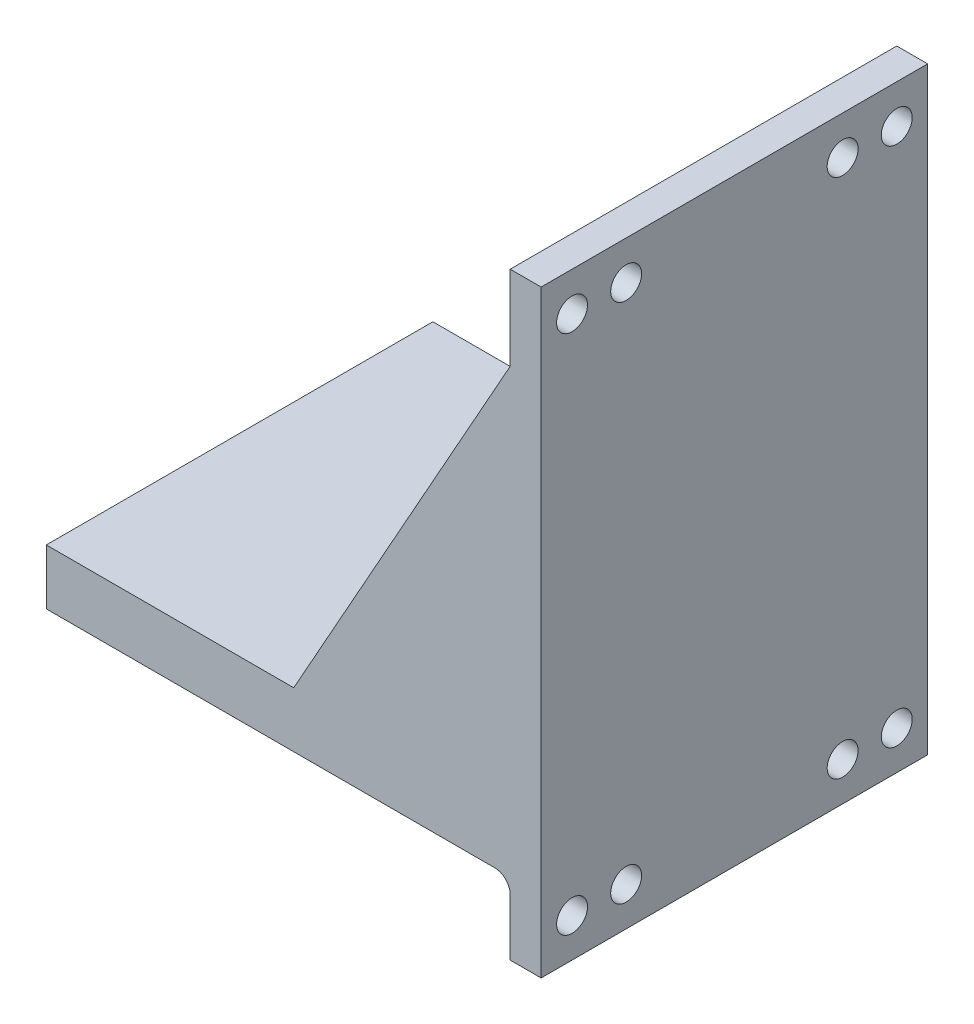
SolidWorks part; units mm, degrees
ref_plane "Front Plane" through (0, 0, 0) normal (0, 0, 1) x (1, 0, 0)
ref_plane "Top Plane" through (0, 0, 0) normal (0, 1, 0) x (1, 0, 0)
ref_plane "Right Plane" through (0, 0, 0) normal (1, 0, 0) x (0, 0, -1)
sketch "Sketch1" plane through (-8, 0, 0) normal (-1, 0, 0) x (0, 0, 1)
  line L0 (30.1107, -33.7) -> (80.1107, -33.7) construction
  line L6 (30.1107, 0) -> (80.1107, 0) construction
  line L8 (30.1107, 38.7) -> (80.1107, 38.7)
  line L9 (30.1107, 38.7) -> (30.1107, -38.7)
  line L10 (30.1107, -38.7) -> (80.1107, -38.7)
  line L11 (80.1107, 38.7) -> (80.1107, -38.7)
  circle A0 centre (34.1107, 33.7) radius 2
  circle A1 centre (41.1107, 33.7) radius 2
  circle A2 centre (69.1107, 33.7) radius 2
  circle A3 centre (76.1107, 33.7) radius 2
  circle A4 centre (34.1107, -33.7) radius 2
  circle A5 centre (41.1107, -33.7) radius 2
  circle A6 centre (69.1107, -33.7) radius 2
  circle A7 centre (76.1107, -33.7) radius 2
  dimension "D1" = 4
  dimension "D2" = 5
extrude "Boss-Extrude1" add sketch "Sketch1" along normal blind 4
sketch "Sketch2" plane through (-12, 0, 0) normal (-1, 0, 0) x (0, 0, 1)
  line L0 (80.1107, -38.7) -> (80.1107, 38.7) construction
  line L1 (80.1107, -29.3571) -> (30.1107, -29.3571)
  line L2 (80.1107, -29.3571) -> (80.1107, -22.1888)
  line L3 (80.1107, -22.1888) -> (30.1107, -22.1888)
  line L4 (30.1107, -29.3571) -> (30.1107, -22.1888)
  line L5 (30.1107, 38.7) -> (30.1107, -38.7) construction
  line L6 (30.1107, -38.7) -> (80.1107, -38.7) construction
  dimension "D1" = 7.1683
  dimension "D2" = 9.3429
extrude "Boss-Extrude2" add sketch "Sketch2" along normal blind 60
ref_plane "Plane1" through (-72, -22.1888, 80.1107) normal (1, 0, 0) x (0, 0, -1)
sketch "Sketch4" plane through (0, 0, 80.1107) normal (0, 0, 1) x (1, 0, 0)
  line L0 (-72, -29.3571) -> (-12, -29.3571) construction
  line L1 (-72, -22.1888) -> (-42, -22.1888)
  line L2 (-72, -22.1888) -> (-72, -29.3571)
  line L3 (-72, -29.3571) -> (-42, -29.3571)
  line L4 (-42, -22.1888) -> (-42, -29.3571)
  dimension "D1" = 30
sketch "Sketch6" plane through (0, -22.1888, 0) normal (0, 1, 0) x (1, 0, 0)
  line L0 (-12, -80.1107) -> (-12, -30.1107) construction
  line L1 (-12, -56.1107) -> (-32, -56.1107)
  line L2 (-12, -56.1107) -> (-12, -30.1107)
  line L3 (-12, -30.1107) -> (-32, -30.1107)
  line L4 (-32, -56.1107) -> (-32, -30.1107)
  line L5 (-72, -30.1107) -> (-12, -30.1107) construction
  dimension "D1" = 20
  dimension "D2" = 26
extrude "Cut-Extrude1" cut sketch "Sketch6" against normal through all
sketch "Sketch7" plane through (0, 0, 80.1107) normal (0, 0, 1) x (1, 0, 0)
  line L0 (-40, -22.1888) -> (-12, 27.8112)
  line L1 (-72, -22.1888) -> (-12, -22.1888) construction
  line L2 (-12, -22.1888) -> (-12, 38.7) construction
  dimension "D1" = 28
  dimension "D2" = 50
rib "Rib1" sketch "Sketch7" sketch "Sketch7" thickness 14 extrusion direction parallel to sketch draft on no parameters "D1"=14
fillet "Fillet2" radius 2 1 edges at (-12, -29.3571, 68.1107)
fillet "Fillet3" radius 12 1 edges at (-32, -25.773, 56.1107)
sketch "Sketch8" plane through (-32, 0, 0) normal (1, 0, 0) x (0, 0, -1)
  line L0 (-30.1107, -29.3571) -> (-44.1107, -29.3571) construction
  line L1 (-30.1107, -22.1888) -> (-43.1107, -22.1888)
  line L2 (-30.1107, -22.1888) -> (-30.1107, -29.3571)
  line L3 (-30.1107, -29.3571) -> (-43.1107, -29.3571)
  line L4 (-43.1107, -22.1888) -> (-43.1107, -29.3571)
  dimension "D1" = 13
extrude "Boss-Extrude3" add sketch "Sketch8" along normal up to surface (20 mm away) up to face at (-12, -5.1469, 62.5107)
fillet "Fillet4" radius 4 1 edges at (-32, -25.773, 43.1107)
ref_plane "Plane2" through (0, 0, 30.1107) normal (0, 0, -1) x (-1, 0, 0)
sketch "Sketch9" plane through (0, 0, 30.1107) normal (0, 0, -1) x (-1, 0, 0)
  line L0 (42, -22.1888) -> (12, 27.8112)
  line L1 (72, -22.1888) -> (12, -22.1888) construction
  line L2 (12, 38.7) -> (12, -22.1888) construction
  line L3 (12, 27.8112) -> (12, -22.1888)
  line L4 (12, -22.1888) -> (42, -22.1888)
  dimension "D1" = 50
extrude "Boss-Extrude4" add sketch "Sketch9" against normal blind 6
fillet "Fillet5" radius 2 1 edges at (-12, -29.3571, 36.6107)
